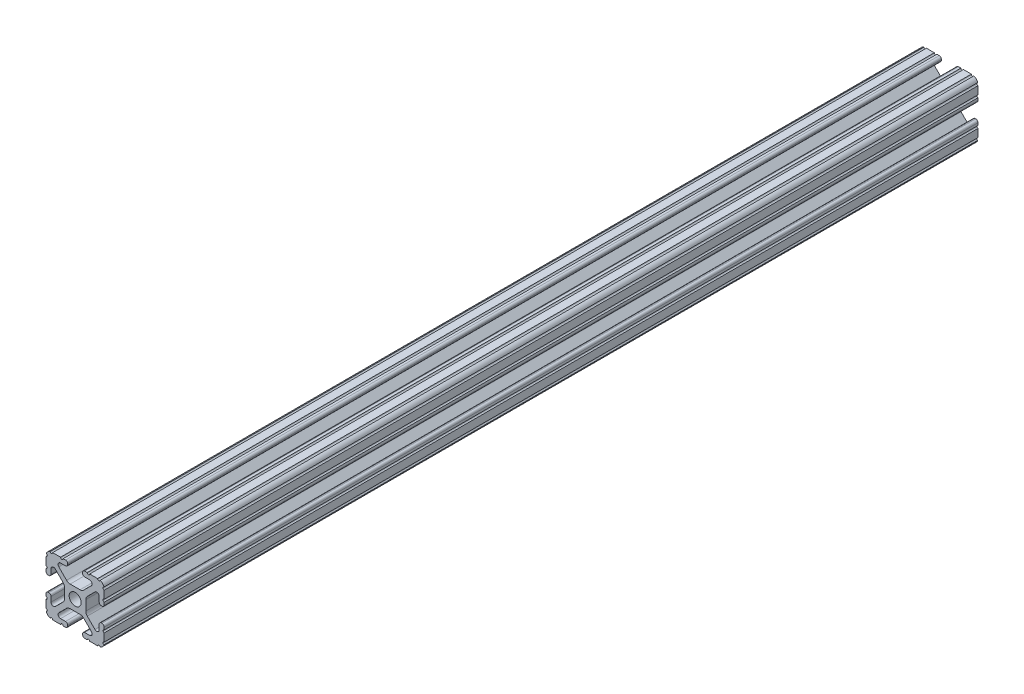
SolidWorks part; units mm, degrees
ref_plane "Front Plane" through (0, 0, 0) normal (0, 0, 1) x (1, 0, 0)
ref_plane "Top Plane" through (0, 0, 0) normal (0, 1, 0) x (1, 0, 0)
ref_plane "Right Plane" through (0, 0, 0) normal (1, 0, 0) x (0, 0, -1)
sketch "Sketch2" plane through (0, 0, 0) normal (0, 0, 1) x (1, 0, 0)
  line L0 (0, 12.7) -> (0, -12.7) construction
  line L1 (-12.7, 0) -> (12.7, 0) construction
  line L2 (3.2512, -12.7) -> (12.7, -12.7)
  line L3 (12.7, -12.7) -> (12.7, -3.2512)
  line L4 (3.2512, -12.7) -> (3.2512, -10.4902)
  line L5 (3.2512, -10.4902) -> (8.9276, -10.4902)
  line L6 (8.9276, -10.4902) -> (3.0856, -4.6482)
  line L7 (0, 0) -> (12.7, -12.7) construction
  line L8 (12.7, -3.2512) -> (10.4902, -3.2512)
  line L9 (10.4902, -3.2512) -> (10.4902, -8.9276)
  line L10 (10.4902, -8.9276) -> (4.6482, -3.0856)
  circle A0 centre (0, 0) radius 2.6035
  arc A1 (6.3485, -10.4902) -> (7.1039, -8.6665) centre (6.3485, -9.4219) ccw construction
  point P8 (0, -4.6482)
  dimension "Center Hole Diameter" = 5.207
  dimension "Rail Height" = 25.4
  dimension "Rail Width" = 25.4
  dimension "T-Slot Width" = 6.5024
  dimension "Slot Inner Width" = 14.8336
  dimension "Thickness" = 2.2098
  dimension "Slot Depth" = 5.842
  dimension "D1" = 2.2098
sketch "Sketch3" plane through (0, 0, 0) normal (1, 0, 0) x (0, 0, -1)
  line L0 (-190.5, -12.7) -> (190.5, -12.7) construction
  line L1 (-171.45, 0) -> (171.45, 0) construction
  dimension "Length" = 381
  dimension "D1" = 342.9
sketch "Sketch4" plane through (0, 0, 0) normal (0, 0, 1) x (1, 0, 0)
  line L0 (4.1904, -12.7) -> (10.1173, -12.7)
  line L1 (3.2512, -12.7) -> (12.7, -12.7) construction
  line L2 (3.2512, -12.7) -> (3.2512, -10.4902) construction
  line L3 (3.2512, -10.4902) -> (8.9276, -10.4902) construction
  line L4 (3.2512, -11.4294) -> (3.2512, -11.7608)
  line L5 (4.1904, -10.4902) -> (6.3485, -10.4902)
  line L6 (0, -4.6482) -> (2.164, -4.6482)
  line L7 (8.9276, -10.4902) -> (3.0856, -4.6482) construction
  line L8 (3.7373, -5.2999) -> (7.1039, -8.6665)
  line L9 (12.7, -12.7) -> (12.7, -3.2512) construction
  line L10 (10.4902, -8.9276) -> (4.6482, -3.0856) construction
  line L11 (10.4902, -3.2512) -> (10.4902, -8.9276) construction
  line L12 (10.4902, -6.3485) -> (10.4902, -4.1904)
  line L13 (12.7, -3.2512) -> (10.4902, -3.2512) construction
  line L14 (11.4294, -3.2512) -> (11.7608, -3.2512)
  line L15 (12.7, -4.1904) -> (12.7, -10.1173)
  line L16 (8.6665, -7.1039) -> (5.2999, -3.7373)
  line L17 (4.6482, 0) -> (4.6482, -2.164)
  line L18 (-12.7, 0) -> (12.7, 0) construction
  line L19 (0, -4.6482) -> (0, -2.6035)
  line L20 (0, 12.7) -> (0, -12.7) construction
  line L21 (4.6482, 0) -> (2.6035, 0)
  arc A0 (3.2512, -11.7608) -> (4.1904, -12.7) centre (4.1904, -11.7608) ccw
  arc A2 (3.2512, -11.4294) -> (4.1904, -10.4902) centre (4.1904, -11.4294) cw
  arc A3 (6.3485, -10.4902) -> (7.1039, -8.6665) centre (6.3485, -9.4219) ccw
  arc A4 (2.164, -4.6482) -> (3.7373, -5.2999) centre (2.164, -6.8732) cw
  arc A5 (10.1173, -12.7) -> (12.7, -10.1173) centre (10.1173, -10.1173) ccw
  arc A6 (8.6665, -7.1039) -> (10.4902, -6.3485) centre (9.4219, -6.3485) ccw
  arc A7 (10.4902, -4.1904) -> (11.4294, -3.2512) centre (11.4294, -4.1904) cw
  arc A8 (11.7608, -3.2512) -> (12.7, -4.1904) centre (11.7608, -4.1904) cw
  arc A9 (5.2999, -3.7373) -> (4.6482, -2.164) centre (6.8732, -2.164) cw
  circle A10 centre (0, 0) radius 2.6035 construction
  arc A11 (0, -2.6035) -> (2.6035, 0) centre (0, 0) ccw
  dimension "D1" = 2.5827
  dimension "D2" = 2.225
  dimension "D3" = 0.9392
extrude "Boss-Extrude1" add sketch "Sketch4" along normal mid plane 381
sketch "Sketch5" plane through (0, 0, 0) normal (0, 0, 1) x (1, 0, 0)
  line L0 (3.2512, -12.7) -> (12.7, -12.7) construction
  line L1 (4.1904, -10.4902) -> (6.3485, -10.4902) construction
  line L3 (0, 0) -> (12.7, -12.7) construction
  line L4 (6.3485, -10.4902) -> (6.3485, -12.7) construction
  line L5 (8.9276, -10.4902) -> (3.0856, -4.6482) construction
  circle A0 centre (10.3562, -12.7) radius 0.5524
  circle A1 centre (5.796, -12.7) radius 0.5524
  circle A2 centre (12.7, -10.3562) radius 0.5524
  circle A3 centre (12.7, -5.796) radius 0.5524
  point P10 (5.2694, -10.4902)
  point P12 (9.4219, -6.3485)
  dimension "D1" = 1.1049
extrude "Cut-Extrude1" cut sketch "Sketch5" against normal through all both and the other way through all
mirror "Mirror1" about plane through (0, 0, 0) normal (1, 0, 0) of bodies 137 134
mirror "Mirror2" about plane through (0, 0, 0) normal (0, 1, 0) of bodies 135
equation "\"D1@Boss-Extrude1\"=\"Length@Sketch3\""
equation "\"D1@Sketch2\"=\"Thickness@Sketch2\""
equation "\"D2@Sketch4\"=\"Slot Inner Width@Sketch2\"*0.15"
equation "\"D1@Sketch4\"=\"D3@Sketch4\"*2.75"
equation "\"D3@Sketch4\"=\"Thickness@Sketch2\"*0.425"
equation "\"D1@Sketch5\"=\"Thickness@Sketch2\"*0.5"
equation "\"D1@Sketch3\"=\"Length@Sketch3\"*0.9"
